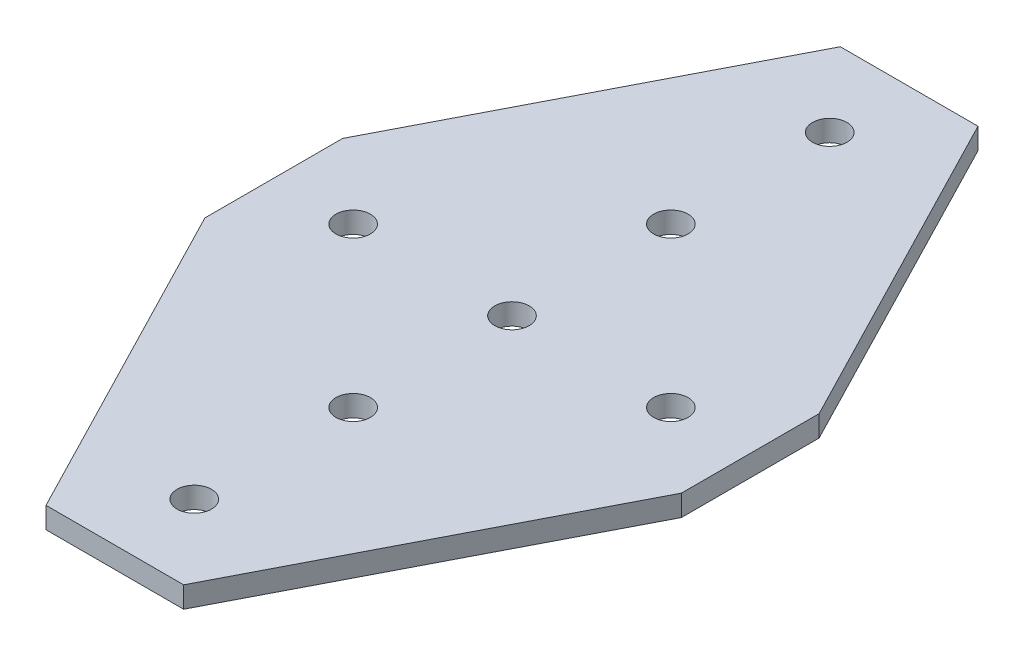
SolidWorks part; units mm, degrees
ref_plane "Front Plane" through (0, 0, 0) normal (0, 0, 1) x (1, 0, 0)
ref_plane "Top Plane" through (0, 0, 0) normal (0, 1, 0) x (1, 0, 0)
ref_plane "Right Plane" through (0, 0, 0) normal (1, 0, 0) x (0, 0, -1)
sketch "Sketch1" plane through (0, 0, 0) normal (0, 1, 0) x (1, 0, 0)
  line L0 (-13, 0) -> (13, 0)
  line L1 (13, 0) -> (45, 62)
  line L2 (45, 62) -> (45, 88)
  line L3 (45, 88) -> (13, 150)
  line L4 (13, 150) -> (-13, 150)
  line L5 (0, -4.0749) -> (0, 14.583) construction
  line L6 (-13, 0) -> (-45, 62)
  line L7 (-45, 62) -> (-45, 88)
  line L8 (-45, 88) -> (-13, 150)
  point P3 (0, 0)
  point P4 (0, 0)
  point P9 (0, 0)
  point P14 (0, 150)
  point P15 (0, 0)
  point P16 (0, 0)
  point P17 (0, 0)
  dimension "D1" = 26
  dimension "D2" = 150
  dimension "D3" = 90
  dimension "D4" = 26
extrude "Boss-Extrude1" add sketch "Sketch1" along normal blind 4
sketch "Sketch3" plane through (0, 4, 0) normal (0, 1, 0) x (1, 0, 0)
  line L0 (0, 150) -> (0, -3.1717) construction
  line L1 (13, 150) -> (-13, 150) construction
  line L2 (-45, 75) -> (45, 75) construction
  line L3 (-45, 88) -> (-45, 62) construction
  line L4 (45, 62) -> (45, 88) construction
  line L5 (0, 75) -> (30, 75) construction
  line L6 (0, 75) -> (-30, 75) construction
  line L7 (0, 75) -> (0, 105) construction
  line L8 (0, 75) -> (0, 45) construction
  circle A0 centre (0, 75) radius 3.25
  circle A1 centre (30, 75) radius 3.25
  circle A2 centre (-30, 75) radius 3.25
  circle A3 centre (0, 105) radius 3.25
  circle A4 centre (0, 135) radius 3.25
  circle A5 centre (0, 45) radius 3.25
  circle A6 centre (0, 15) radius 3.25
  dimension "D1" = 6.5
  dimension "D3" = 30
  dimension "D5" = 30
  dimension "D7" = 30
  dimension "D9" = 30
  dimension "D2" = 2
  dimension "D4" = 2
  dimension "D6" = 3
  dimension "D8" = 3
extrude "Cut-Extrude1" cut sketch "Sketch3" against normal through all
